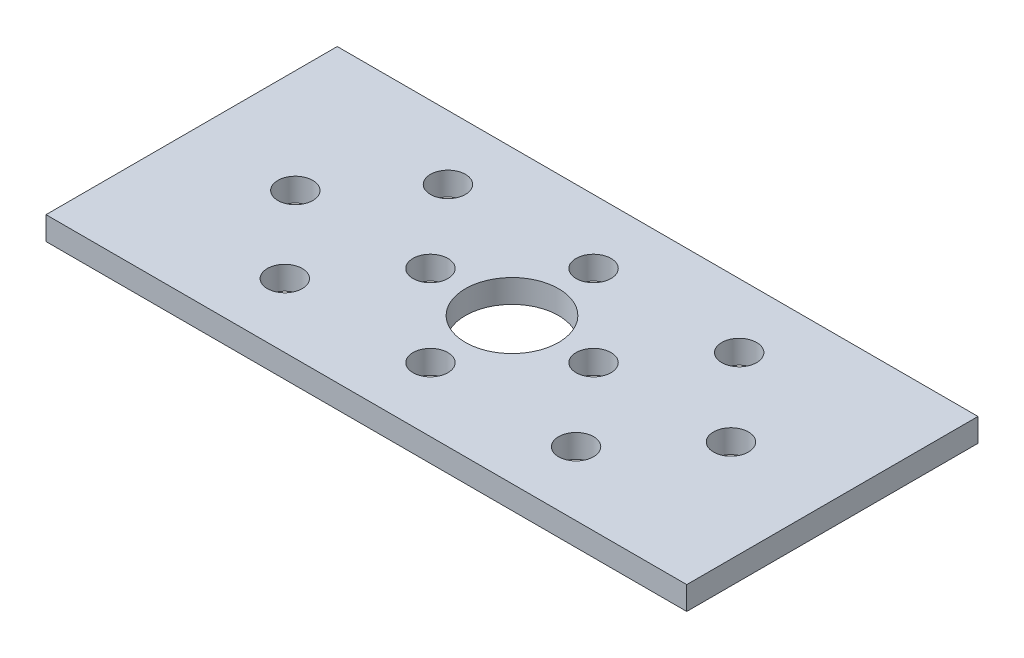
SolidWorks part; units mm, degrees
ref_plane "前视基准面" through (0, 0, 0) normal (0, 0, 1) x (1, 0, 0)
ref_plane "上视基准面" through (0, 0, 0) normal (0, 1, 0) x (1, 0, 0)
ref_plane "右视基准面" through (0, 0, 0) normal (1, 0, 0) x (0, 0, -1)
other "Configuration Table"
sketch "草图1" plane through (0, 0, 0) normal (0, 1, 0) x (1, 0, 0)
  line L0 (-27.4987, 0) -> (27.4987, 0) construction
  line L5 (0, 18.7431) -> (0, 0) construction
  line L6 (-27.5, -12.5) -> (27.5, -12.5)
  line L7 (-27.5, -12.5) -> (-27.5, 12.5)
  line L8 (-27.5, 12.5) -> (27.5, 12.5)
  line L9 (27.5, -12.5) -> (27.5, 12.5)
  line L10 (-27.5, -12.5) -> (27.5, 12.5) construction
  line L11 (-27.5, 12.5) -> (27.5, -12.5) construction
  line L12 (0, 0) -> (0, -15.368) construction
  circle A7 centre (0, 0) radius 7 construction
  circle A8 centre (0, 7) radius 1.5
  circle A9 centre (7, 0) radius 1.5
  circle A10 centre (0, -7) radius 1.5
  circle A11 centre (-7, 0) radius 1.5
  circle A12 centre (-18.5987, 0) radius 1.5
  circle A13 centre (0, 0) radius 4
  circle A14 centre (18.7959, 0) radius 1.5
  circle A15 centre (12.5, 7) radius 1.5
  circle A16 centre (12.5, -7) radius 1.5
  circle A17 centre (-12.5, -7) radius 1.5
  circle A18 centre (-12.5, 7) radius 1.5
  dimension "D1" = 3
  dimension "D2" = 8
  dimension "D3" = 14
  dimension "D8" = 3
  dimension "D4" = 18.7959
  dimension "D5" = 18.5987
  dimension "D6" = 55
  dimension "D7" = 25
  dimension "D9" = 15
extrude "凸台-拉伸1" add sketch "草图1" along normal blind 2
